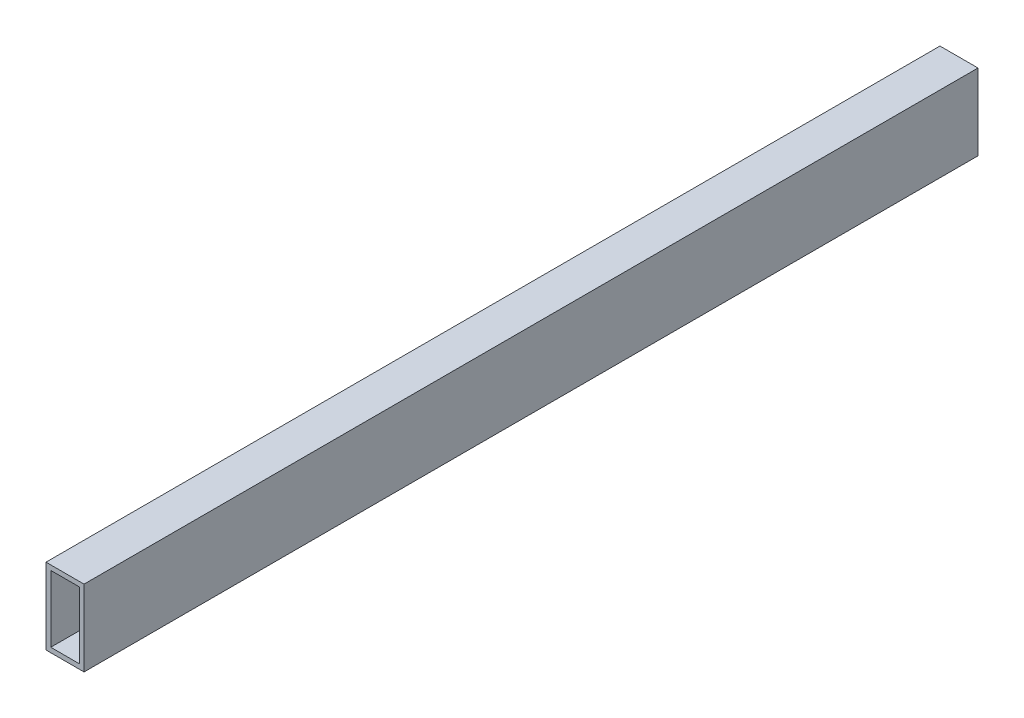
SolidWorks part; units mm, degrees
ref_plane "Front Plane" through (0, 0, 0) normal (0, 0, 1) x (1, 0, 0)
ref_plane "Top Plane" through (0, 0, 0) normal (0, 1, 0) x (1, 0, 0)
ref_plane "Right Plane" through (0, 0, 0) normal (1, 0, 0) x (0, 0, -1)
sketch "Sketch1" plane through (0, 0, 0) normal (0, 0, 1) x (1, 0, 0)
  line L0 (-9.525, 22.225) -> (9.525, 22.225)
  line L1 (-12.7, -25.4) -> (12.7, -25.4)
  line L2 (-12.7, -25.4) -> (-12.7, 25.4)
  line L3 (-12.7, 25.4) -> (12.7, 25.4)
  line L4 (12.7, -25.4) -> (12.7, 25.4)
  line L5 (-12.7, -25.4) -> (12.7, 25.4) construction
  line L6 (-12.7, 25.4) -> (12.7, -25.4) construction
  line L7 (9.525, -22.225) -> (9.525, 22.225)
  line L8 (-9.525, -22.225) -> (9.525, -22.225)
  line L9 (-9.525, -22.225) -> (-9.525, 22.225)
  point P0 (0, 0)
  dimension "D1" = 50.8
  dimension "D2" = 25.4
  dimension "D3" = 3.175
extrude "Boss-Extrude1" add sketch "Sketch1" along normal blind 596.9
